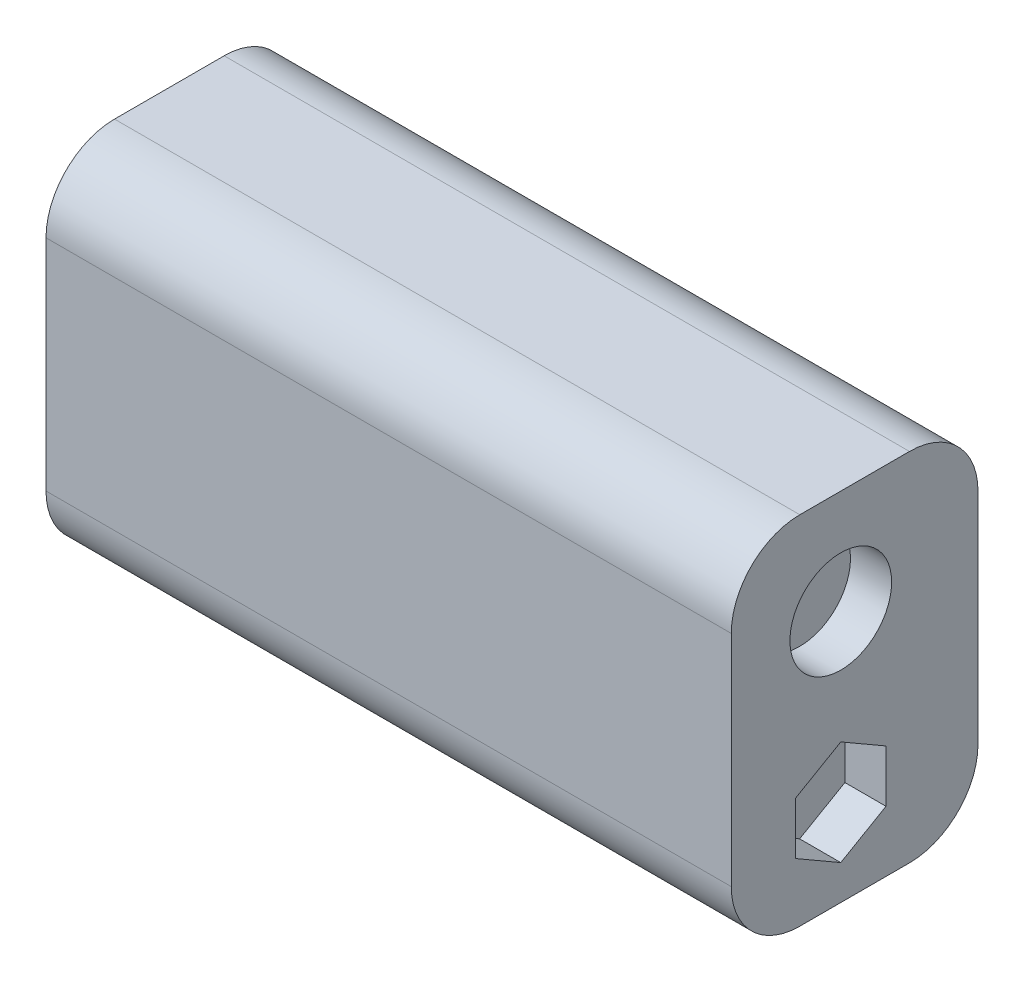
SolidWorks part; units mm, degrees
ref_plane "Front Plane" through (0, 0, 0) normal (0, 0, 1) x (1, 0, 0)
ref_plane "Top Plane" through (0, 0, 0) normal (0, 1, 0) x (1, 0, 0)
ref_plane "Right Plane" through (0, 0, 0) normal (1, 0, 0) x (0, 0, -1)
sketch "Sketch1" plane through (0, 0, 0) normal (0, 0, 1) x (1, 0, 0)
  line L1 (-25, -13) -> (25, -13)
  line L2 (-25, -13) -> (-25, 13)
  line L3 (-25, 13) -> (25, 13)
  line L4 (25, -13) -> (25, 13)
  line L5 (-25, -13) -> (25, 13) construction
  line L6 (-25, 13) -> (25, -13) construction
  point P0 (0, 0)
  dimension "D1" = 50
  dimension "D2" = 26
extrude "Boss-Extrude1" add sketch "Sketch1" along normal blind 18
sketch "Sketch2" plane through (25, 0, 0) normal (1, 0, 0) x (0, 0, -1)
  line L1 (-10.0124, -2.8487) -> (-13.3136, -4.7546)
  line L2 (-13.3136, -4.7546) -> (-13.3136, -8.5665)
  line L3 (-13.3136, -8.5665) -> (-10.0124, -10.4725)
  line L4 (-10.0124, -10.4725) -> (-6.7112, -8.5665)
  line L5 (-6.7112, -8.5665) -> (-6.7112, -4.7546)
  line L6 (-6.7112, -4.7546) -> (-10.0124, -2.8487)
  circle A0 centre (-10.0124, -6.6606) radius 3.3012 construction
  circle A1 centre (-10.0124, 5.3954) radius 3.7098
extrude "Cut-Extrude1" cut sketch "Sketch2" against normal blind 3
fillet "Fillet1" radius 5 4 edges at (0, -13, 0) (0, -13, 18) (0, 13, 0) (0, 13, 18)
sketch "Sketch3" plane through (-25, 0, 0) normal (-1, 0, 0) x (0, 0, 1)
  line L0 (0, 2) -> (0, -8)
  line L2 (0, -4) -> (7, -4)
  line L4 (0, 8) -> (0, -8) construction
  line L5 (7, -4) -> (7, 2)
  line L6 (7, -4) -> (7, -10)
  line L7 (7, -10) -> (0.4174, -10)
  line L8 (7, 2) -> (0, 2)
  arc A0 (0, -8) -> (5, -13) centre (5, -8) ccw construction
  line M5 (0, 8) -> (0, -8)
  arc M6 (0, -8) -> (5, -13) centre (5, -8) ccw
  dimension "D2" = 7
  dimension "D3" = 6
  dimension "D4" = 6
extrude "Cut-Extrude4" cut sketch "Sketch3" against normal blind 5 contours L7 L6 L2 L0 M6 | L5 L8 L2 M5
